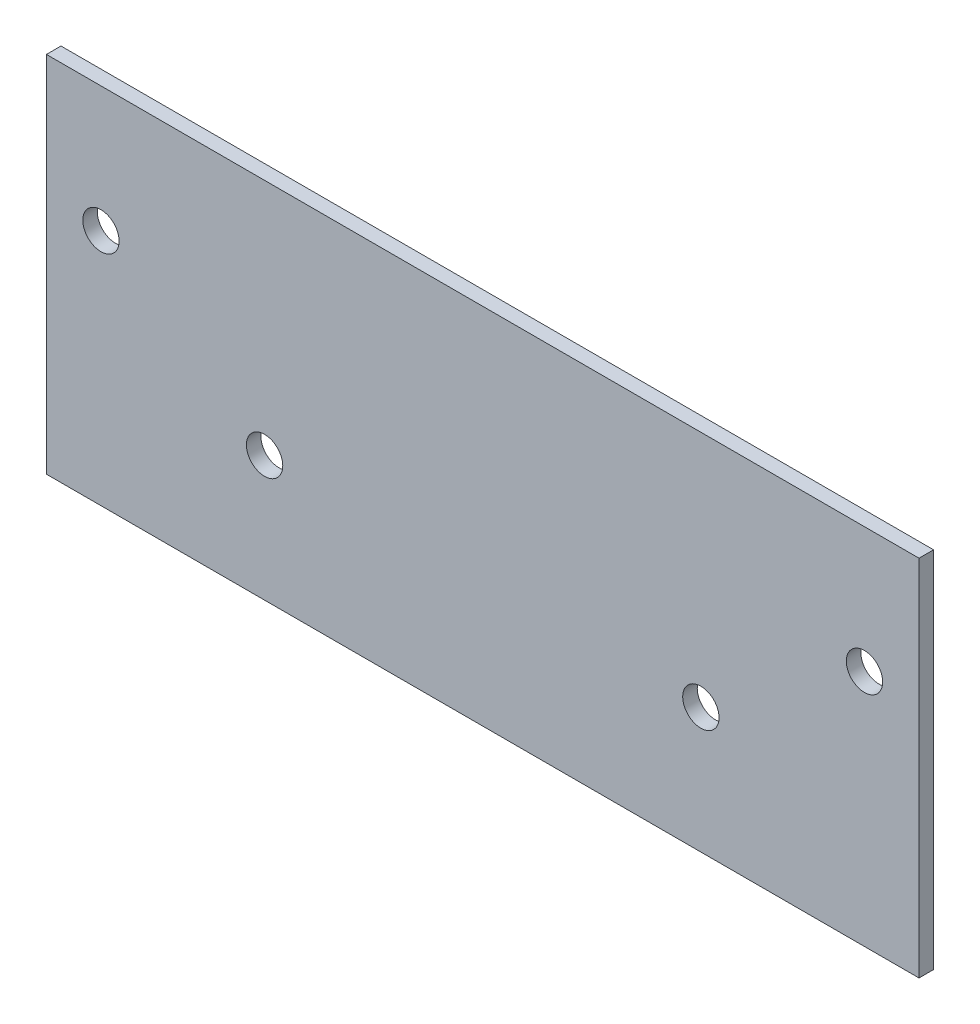
SolidWorks part; units mm, degrees
ref_plane "Ön Düzlem" through (0, 0, 0) normal (0, 0, 1) x (1, 0, 0)
ref_plane "Üst Düzlem" through (0, 0, 0) normal (0, 1, 0) x (1, 0, 0)
ref_plane "Sağ Düzlem" through (0, 0, 0) normal (1, 0, 0) x (0, 0, -1)
sketch "Çizim1" plane through (0, 0, 0) normal (0, 0, 1) x (1, 0, 0)
  line L0 (0, 0) -> (0, 25) construction
  line L1 (-60, 25) -> (60, 25)
  line L2 (-60, 25) -> (-60, -25)
  line L3 (-60, -25) -> (60, -25)
  line L4 (60, 25) -> (60, -25)
  line L5 (0, 0) -> (-60, 0) construction
  circle A0 centre (-52.5, 7.75) radius 2.5
  circle A1 centre (52.5, 7.75) radius 2.5
  circle A2 centre (-30, -7.75) radius 2.5
  circle A3 centre (30, -7.75) radius 2.5
  dimension "D5" = 17.25
  dimension "D6" = 7.5
  dimension "D7" = 5
  dimension "D8" = 5
  dimension "D9" = 17.25
  dimension "D10" = 30
  dimension "D1" = 50
  dimension "D2" = 120
  dimension "D3" = 25
  dimension "D4" = 60
extrude "Yükseklik-Ekstrüzyon1" add sketch "Çizim1" along normal blind 2
